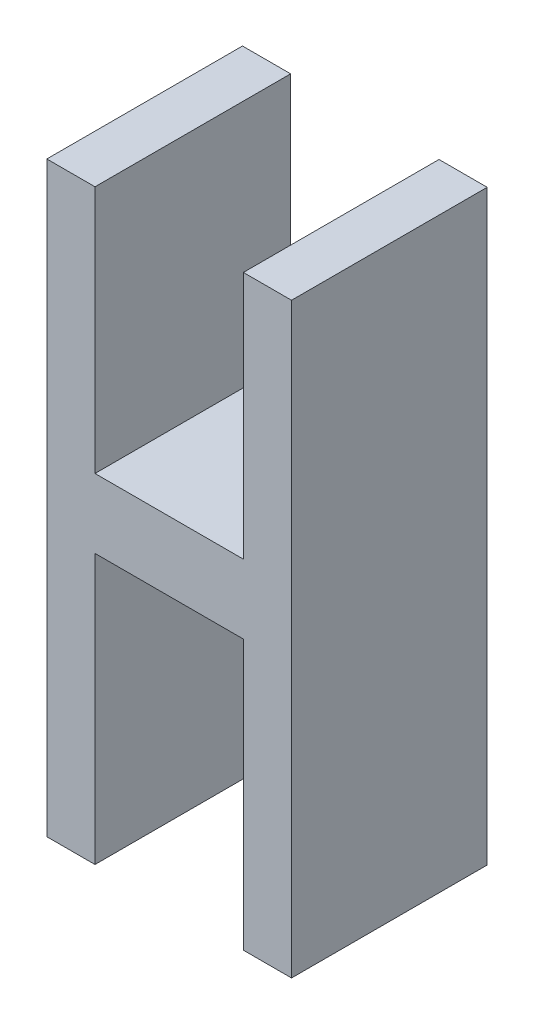
SolidWorks part; units mm, degrees
ref_plane "Front Plane" through (0, 0, 0) normal (0, 0, 1) x (1, 0, 0)
ref_plane "Top Plane" through (0, 0, 0) normal (0, 1, 0) x (1, 0, 0)
ref_plane "Right Plane" through (0, 0, 0) normal (1, 0, 0) x (0, 0, -1)
sketch "Sketch3" plane through (0, 0, 0) normal (0, 0, 1) x (1, 0, 0)
  text T0 "H" font "Consolas" height 914.4
extrude "Boss-Extrude1" add sketch "Sketch3" against normal blind 304.8
shell "Shell1" thickness 2.54
sketch "Sketch4" plane through (0, 0, -2.54) normal (0, 0, -1) x (-1, 0, 0)
  line L0 (-46.6425, 0) -> (-46.6425, 914.4) construction
  line L1 (-427.8671, 914.4) -> (-427.8671, 0) construction
  line L2 (-262.6548, 448.2304) -> (-211.8548, 448.2304)
  line L3 (-262.6548, 448.2304) -> (-262.6548, 499.0304)
  line L4 (-262.6548, 499.0304) -> (-211.8548, 499.0304)
  line L5 (-211.8548, 448.2304) -> (-211.8548, 499.0304)
  dimension "D3" = 50.8
  dimension "D4" = 50.8
extrude "Boss-Extrude2" add sketch "Sketch4" along normal blind 381
sketch "Sketch5" plane through (0, 419.7824, 0) normal (0, -1, 0) x (1, 0, 0)
  line L0 (352.8245, -304.8) -> (121.6851, -304.8) construction
  line L1 (224.4425, -304.8) -> (254.9225, -304.8)
  line L2 (224.4425, -304.8) -> (224.4425, -25.4)
  line L3 (224.4425, -25.4) -> (254.9225, -25.4)
  line L4 (254.9225, -304.8) -> (254.9225, -25.4)
  line L7 (352.8245, 0) -> (121.6851, 0) construction
  line L8 (46.6425, -304.8) -> (46.6425, 0) construction
  dimension "D1" = 30.48
  dimension "D2" = 177.8
  dimension "D3" = 25.4
extrude "Cut-Extrude1" cut sketch "Sketch5" against normal blind 7.62
sketch "Sketch6" plane through (0, 0, -383.54) normal (0, 0, -1) x (-1, 0, 0)
  line L0 (-262.6548, 499.0304) -> (-262.6548, 448.2304) construction
  line L1 (-269.0048, 441.8804) -> (-205.5048, 441.8804)
  line L2 (-269.0048, 441.8804) -> (-269.0048, 505.3804)
  line L3 (-269.0048, 505.3804) -> (-205.5048, 505.3804)
  line L4 (-205.5048, 441.8804) -> (-205.5048, 505.3804)
  line L5 (-269.0048, 441.8804) -> (-205.5048, 505.3804) construction
  line L6 (-269.0048, 505.3804) -> (-205.5048, 441.8804) construction
  line L7 (-262.6548, 448.2304) -> (-211.8548, 448.2304) construction
  point P0 (-237.2548, 473.6304)
  dimension "D1" = 63.5
  dimension "D2" = 63.5
  dimension "D3" = 6.35
  dimension "D4" = 6.35
extrude "Boss-Extrude3" add sketch "Sketch6" along normal blind 2.54
sketch "Sketch7" plane through (0, 0, -386.08) normal (0, 0, -1) x (-1, 0, 0)
  line L0 (-269.0048, 441.8804) -> (-205.5048, 441.8804) construction
  line L1 (-261.3848, 441.8804) -> (-256.3048, 441.8804)
  line L2 (-261.3848, 441.8804) -> (-261.3848, 505.3804)
  line L3 (-261.3848, 505.3804) -> (-256.3048, 505.3804)
  line L4 (-256.3048, 441.8804) -> (-256.3048, 505.3804)
  line L5 (-205.5048, 505.3804) -> (-269.0048, 505.3804) construction
  line L6 (-269.0048, 505.3804) -> (-269.0048, 441.8804) construction
  line L7 (-218.2048, 441.8804) -> (-213.1248, 441.8804)
  line L8 (-218.2048, 441.8804) -> (-218.2048, 505.3804)
  line L9 (-218.2048, 505.3804) -> (-213.1248, 505.3804)
  line L10 (-213.1248, 441.8804) -> (-213.1248, 505.3804)
  dimension "D1" = 38.1
  dimension "D2" = 7.62
  dimension "D3" = 5.08
  dimension "D4" = 5.08
extrude "Boss-Extrude4" add sketch "Sketch7" along normal blind 50.8
sketch "Sketch8" plane through (256.3048, 0, 0) normal (-1, 0, 0) x (0, 0, 1)
  line L0 (-436.88, 441.8804) -> (-436.88, 505.3804) construction
  line L1 (-436.88, 441.8804) -> (-386.08, 441.8804) construction
  circle A0 centre (-411.48, 473.6304) radius 19.05
  point P4 (-436.88, 473.6304)
  dimension "D3" = 38.1
  dimension "D1" = 25.4
  dimension "D2" = 31.75
extrude "Boss-Extrude5" add sketch "Sketch8" along normal up to next
